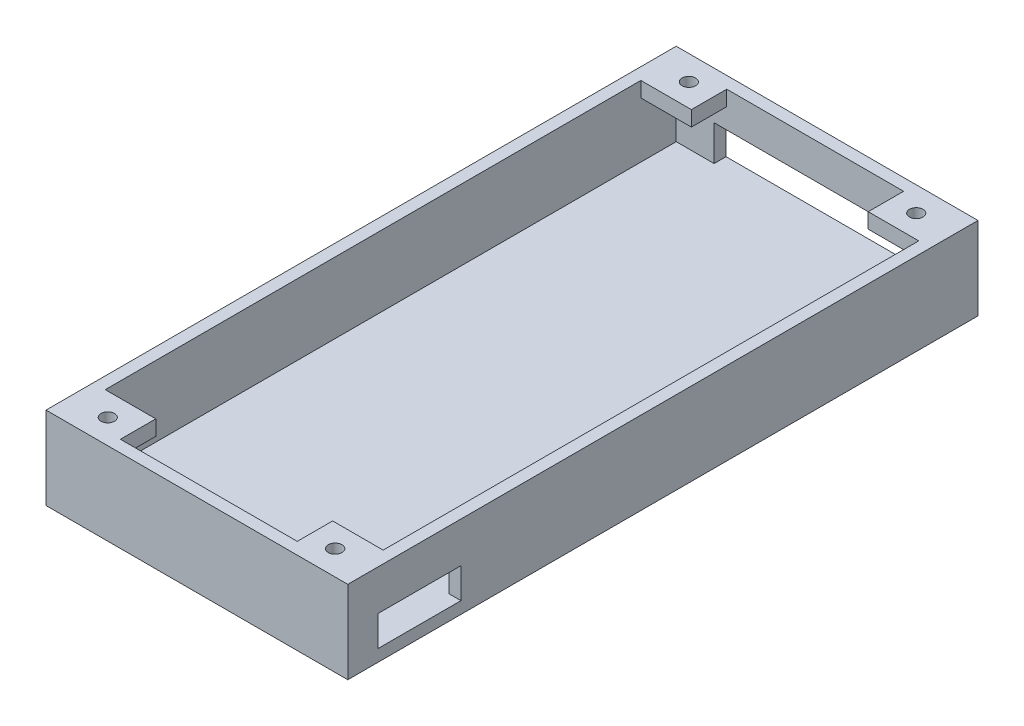
SolidWorks part; units mm, degrees
ref_plane "Front Plane" through (0, 0, 0) normal (0, 0, 1) x (1, 0, 0)
ref_plane "Top Plane" through (0, 0, 0) normal (0, 1, 0) x (1, 0, 0)
ref_plane "Right Plane" through (0, 0, 0) normal (1, 0, 0) x (0, 0, -1)
sketch "Sketch1" plane through (0, 0, 0) normal (0, 1, 0) x (1, 0, 0)
  line L0 (-37.925, 79.2) -> (37.925, 79.2)
  line L1 (-34.925, 76.2) -> (34.925, 76.2)
  line L2 (-34.925, 76.2) -> (-34.925, -76.2)
  line L3 (-34.925, -76.2) -> (34.925, -76.2)
  line L4 (34.925, 76.2) -> (34.925, -76.2)
  line L5 (-34.925, 76.2) -> (34.925, -76.2) construction
  line L6 (-34.925, -76.2) -> (34.925, 76.2) construction
  line L7 (37.925, 79.2) -> (37.925, -79.2)
  line L8 (-37.925, -79.2) -> (37.925, -79.2)
  line L9 (-37.925, 79.2) -> (-37.925, -79.2)
  point P0 (0, 0)
  dimension "D1" = 69.85
  dimension "D2" = 152.4
  dimension "D3" = 3
extrude "Boss-Extrude1" add sketch "Sketch1" along normal blind 3 contours L9 L8 L7 L0
sketch "Sketch2" plane through (0, 3, 0) normal (0, 1, 0) x (1, 0, 0)
  line L1 (-37.925, 79.2) -> (37.925, 79.2)
  line L2 (-37.925, 79.2) -> (-37.925, -79.2)
  line L3 (-37.925, -79.2) -> (37.925, -79.2)
  line L4 (37.925, 79.2) -> (37.925, -79.2)
  line L5 (-37.925, 79.2) -> (37.925, -79.2) construction
  line L6 (-37.925, -79.2) -> (37.925, 79.2) construction
  line L7 (-34.925, 76.2) -> (34.925, 76.2)
  line L8 (-34.925, 76.2) -> (-34.925, -76.2)
  line L9 (-34.925, -76.2) -> (34.925, -76.2)
  line L10 (34.925, 76.2) -> (34.925, -76.2)
  line L11 (-34.925, 76.2) -> (34.925, -76.2) construction
  line L12 (-34.925, -76.2) -> (34.925, 76.2) construction
  point P0 (0, 0)
  point P7 (0, 0)
  dimension "D1" = 152.4
  dimension "D2" = 69.85
extrude "Boss-Extrude2" add sketch "Sketch2" along normal blind 17.78
sketch "Sketch3" plane through (0, 20.78, 0) normal (0, 1, 0) x (1, 0, 0)
  line L1 (-34.925, 76.2) -> (-22.225, 76.2)
  line L2 (-34.925, 76.2) -> (-34.925, 67.31)
  line L3 (-34.925, 67.31) -> (-22.225, 67.31)
  line L4 (-22.225, 76.2) -> (-22.225, 67.31)
  line L5 (-34.925, -76.2) -> (-22.225, -76.2)
  line L6 (-34.925, -76.2) -> (-34.925, -67.31)
  line L7 (-34.925, -67.31) -> (-22.225, -67.31)
  line L8 (-22.225, -76.2) -> (-22.225, -67.31)
  line L9 (34.925, 76.2) -> (22.225, 76.2)
  line L10 (34.925, 76.2) -> (34.925, 67.31)
  line L11 (34.925, 67.31) -> (22.225, 67.31)
  line L12 (22.225, 76.2) -> (22.225, 67.31)
  line L13 (34.925, -76.2) -> (22.225, -76.2)
  line L14 (34.925, -76.2) -> (34.925, -67.31)
  line L15 (34.925, -67.31) -> (22.225, -67.31)
  line L16 (22.225, -76.2) -> (22.225, -67.31)
  point P20 (-28.575, 70.485)
  point P21 (-28.575, -73.025)
  point P22 (28.575, -73.025)
  point P23 (28.575, 73.025)
  dimension "D1" = 12.7
  dimension "D2" = 8.89
  dimension "D3" = 8.89
  dimension "D4" = 12.7
  dimension "D5" = 12.7
  dimension "D6" = 8.89
  dimension "D7" = 8.89
  dimension "D8" = 12.7
  dimension "D9" = 6.35
  dimension "D10" = 3.175
  dimension "D11" = 6.35
  dimension "D12" = 3.175
  dimension "D13" = 6.35
  dimension "D14" = 3.175
  dimension "D15" = 6.35
  dimension "D16" = 3.175
extrude "Boss-Extrude3" add sketch "Sketch3" against normal blind 3.81
sketch "Sketch4" plane through (0, 20.78, 0) normal (0, 1, 0) x (1, 0, 0)
  line L0 (-22.225, 67.31) -> (-22.225, 76.2) construction
  line L3 (-22.225, -76.2) -> (-22.225, -67.31) construction
  line L4 (22.225, -67.31) -> (22.225, -76.2) construction
  line L7 (22.225, 76.2) -> (22.225, 67.31) construction
  line L9 (22.225, 76.2) -> (-22.225, 76.2) construction
  line L10 (-34.925, -76.2) -> (34.925, -76.2) construction
  line L11 (34.925, 76.2) -> (-34.925, 76.2) construction
  line L12 (-22.225, -76.2) -> (22.225, -76.2) construction
  circle A0 centre (-28.575, 73.025) radius 1.7
  circle A1 centre (28.575, 73.025) radius 1.7
  circle A2 centre (28.575, -73.025) radius 1.72
  circle A3 centre (-28.575, -73.025) radius 1.7
  point P0 (-28.575, 73.025)
  point P1 (-28.575, -73.025)
  point P2 (28.575, -73.025)
  point P3 (28.575, 73.025)
  dimension "D9" = 3.4
  dimension "D10" = 3.4
  dimension "D11" = 3.4
  dimension "D12" = 3.44
  dimension "D1" = 6.35
  dimension "D2" = 3.175
  dimension "D3" = 3.175
  dimension "D4" = 6.35
  dimension "D5" = 6.35
  dimension "D6" = 3.175
  dimension "D7" = 3.175
  dimension "D8" = 6.35
sketch "Sketch6" plane through (37.925, 0, 0) normal (1, 0, 0) x (0, 0, -1)
  line L1 (-12.7, 3) -> (12.7, 3)
  line L2 (-12.7, 3) -> (-12.7, 10.62)
  line L3 (-12.7, 10.62) -> (12.7, 10.62)
  line L4 (12.7, 3) -> (12.7, 10.62)
  line L6 (79.2, 0) -> (-79.2, 0) construction
  point P6 (0, 3)
  dimension "D1" = 7.62
  dimension "D2" = 3
  dimension "D3" = 25.4
sketch "Sketch7" plane through (0, 0, 0) normal (0, -1, 0) x (1, 0, 0)
  line L1 (-25.4, 21.35) -> (25.4, 21.35)
  line L2 (-25.4, 21.35) -> (-25.4, -21.35)
  line L3 (-25.4, -21.35) -> (25.4, -21.35)
  line L4 (25.4, 21.35) -> (25.4, -21.35)
  line L5 (-25.4, 21.35) -> (25.4, -21.35) construction
  line L6 (-25.4, -21.35) -> (25.4, 21.35) construction
  point P0 (0, 0)
  dimension "D1" = 42.7
  dimension "D2" = 50.8
extrude "Boss-Extrude4" add sketch "Sketch7" along normal blind 6.35
sketch "Sketch8" plane through (0, 0, 21.35) normal (0, 0, 1) x (1, 0, 0)
  line L0 (-3.81, 0) -> (-3.81, -3.175)
  line L3 (25.4, 0) -> (-25.4, 0) construction
  line L4 (-3.81, -3.175) -> (-11.43, -3.175)
  line L5 (-11.43, -3.175) -> (-11.43, -6.35)
  line L6 (25.4, -6.35) -> (-25.4, -6.35) construction
  line L7 (-11.43, -6.35) -> (11.43, -6.35)
  line L8 (11.43, -6.35) -> (11.43, -3.175)
  line L9 (11.43, -3.175) -> (3.81, -3.175)
  line L10 (3.81, -3.175) -> (3.81, 0)
  line M5 (25.4, 0) -> (-25.4, 0)
  line M6 (-25.4, 0) -> (-25.4, -6.35)
  line M7 (-25.4, -6.35) -> (25.4, -6.35)
  line M8 (25.4, -6.35) -> (25.4, 0)
  dimension "D1" = 3.81
  dimension "D2" = 3.81
  dimension "D3" = 7.62
  dimension "D4" = 7.62
  dimension "D5" = 3.175
  dimension "D6" = 3.175
extrude "Cut-Extrude2" cut sketch "Sketch8" against normal through all and the other way through all contours L5 L4 L0 M5 M6 M7 | L10 L9 L8 M7 M8 M5
sketch "Sketch9" plane through (0, -6.35, 0) normal (0, -1, 0) x (1, 0, 0)
  line L0 (-11.43, 21.35) -> (-11.43, -21.35) construction
  line L1 (-11.43, 11.65) -> (11.43, 11.65)
  line L2 (-11.43, 11.65) -> (-11.43, 21.35)
  line L3 (-11.43, 21.35) -> (11.43, 21.35)
  line L4 (11.43, 11.65) -> (11.43, 21.35)
  dimension "D1" = 9.7
extrude "Cut-Extrude3" cut sketch "Sketch9" against normal up to surface (6.35 mm away)
extrude "Cut-Extrude4" cut sketch "Sketch4" against normal up to next contours A1 | A2 | A3 | A0
sketch "Sketch10" plane through (0, 0, -79.2) normal (0, 0, -1) x (-1, 0, 0)
  line L0 (37.925, 0) -> (-37.925, 0) construction
  line L1 (-25.4, 3) -> (25.4, 3)
  line L2 (-25.4, 3) -> (-25.4, 11.89)
  line L3 (-25.4, 11.89) -> (25.4, 11.89)
  line L4 (25.4, 3) -> (25.4, 11.89)
  point P6 (0, 3)
  dimension "D1" = 3
  dimension "D2" = 8.89
  dimension "D3" = 50.8
extrude "Cut-Extrude5" cut sketch "Sketch10" against normal up to next
sketch "Sketch11" plane through (37.925, 0, 0) normal (1, 0, 0) x (0, 0, -1)
  line L0 (79.2, 0) -> (-79.2, 0) construction
  line L1 (-71.58, 3) -> (-50.752, 3)
  line L2 (-71.58, 3) -> (-71.58, 10.62)
  line L3 (-71.58, 10.62) -> (-50.752, 10.62)
  line L4 (-50.752, 3) -> (-50.752, 10.62)
  line L5 (-79.2, 20.78) -> (-79.2, 0) construction
  dimension "D1" = 3
  dimension "D2" = 7.62
  dimension "D3" = 28.448
  dimension "D4" = 7.62
extrude "Cut-Extrude6" cut sketch "Sketch11" against normal up to next
